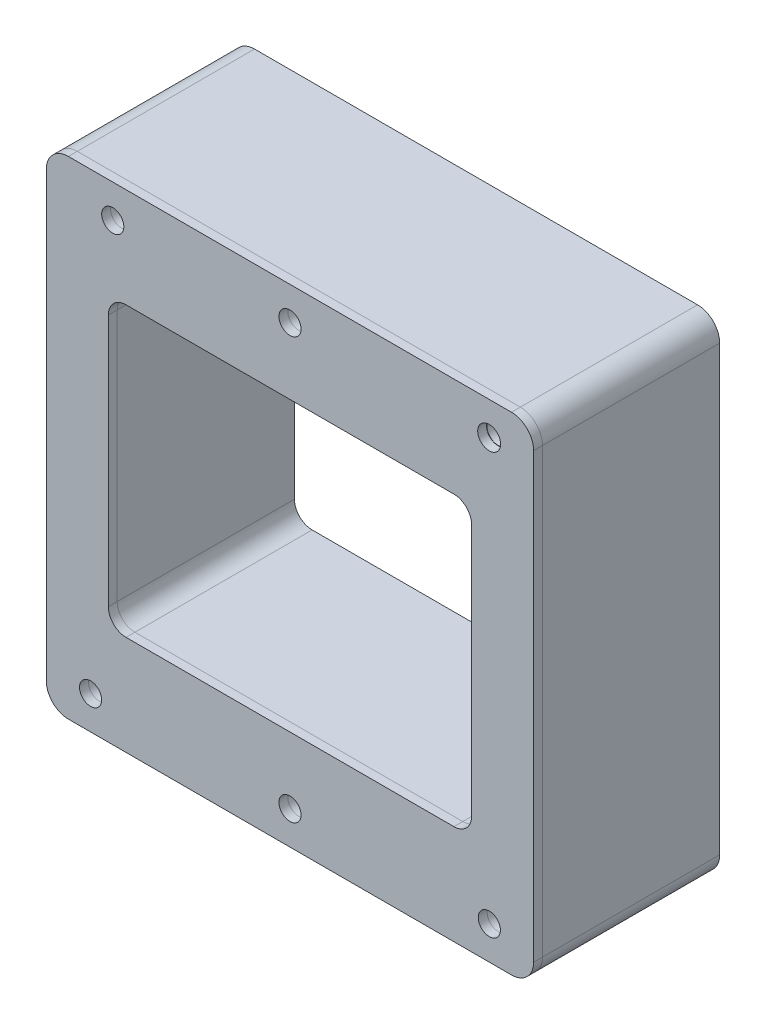
SolidWorks part; units mm, degrees
ref_plane "Front Plane" through (0, 0, 0) normal (0, 0, 1) x (1, 0, 0)
ref_plane "Top Plane" through (0, 0, 0) normal (0, 1, 0) x (1, 0, 0)
ref_plane "Right Plane" through (0, 0, 0) normal (1, 0, 0) x (0, 0, -1)
sketch "Croquis2" plane through (0, 0, 0) normal (0, 0, 1) x (1, 0, 0)
  line L16 (734.8657, 868.0574) -> (734.8657, 925.0574)
  line L17 (656.8657, 864.0574) -> (730.8657, 864.0574)
  line L18 (652.8657, 925.0574) -> (652.8657, 868.0574)
  line L19 (730.8657, 929.0574) -> (656.8657, 929.0574)
  line L24 (643.8623, 841.5574) -> (743.8623, 841.5574)
  line L25 (748.8623, 846.5574) -> (748.8623, 946.5574)
  line L26 (743.8623, 951.5574) -> (643.8623, 951.5574)
  line L27 (638.8623, 946.5574) -> (638.8623, 846.5574)
  circle A1 centre (693.8623, 944.0574) radius 2.5
  circle A2 centre (653.8623, 944.0574) radius 2.5
  circle A3 centre (738.8214, 944.0807) radius 2.5
  circle A4 centre (738.8623, 849.0574) radius 2.5
  circle A5 centre (693.8623, 849.0574) radius 2.5
  circle A6 centre (648.8623, 849.0574) radius 2.5
  arc A16 (730.8657, 864.0574) -> (734.8657, 868.0574) centre (730.8657, 868.0574) ccw
  arc A17 (652.8657, 868.0574) -> (656.8657, 864.0574) centre (656.8657, 868.0574) ccw
  arc A18 (656.8657, 929.0574) -> (652.8657, 925.0574) centre (656.8657, 925.0574) ccw
  arc A19 (734.8657, 925.0574) -> (730.8657, 929.0574) centre (730.8657, 925.0574) ccw
  arc A36 (743.8623, 841.5574) -> (748.8623, 846.5574) centre (743.8623, 846.5574) ccw
  arc A37 (748.8623, 946.5574) -> (743.8623, 951.5574) centre (743.8623, 946.5574) ccw
  arc A38 (643.8623, 951.5574) -> (638.8623, 946.5574) centre (643.8623, 946.5574) ccw
  arc A39 (638.8623, 846.5574) -> (643.8623, 841.5574) centre (643.8623, 846.5574) ccw
extrude "Saliente-Extruir1" add sketch "Croquis2" along normal blind 40
sketch "Croquis3" plane through (0, 0, 40) normal (0, 0, 1) x (1, 0, 0)
  line L4 (730.8657, 929.0574) -> (656.8657, 929.0574)
  line L5 (734.8657, 868.0574) -> (734.8657, 925.0574)
  line L6 (656.8657, 864.0574) -> (730.8657, 864.0574)
  line L7 (652.8657, 925.0574) -> (652.8657, 868.0574)
  line L8 (730.8657, 929.0574) -> (656.8657, 929.0574)
  line L9 (734.8657, 868.0574) -> (734.8657, 925.0574)
  line L10 (656.8657, 864.0574) -> (730.8657, 864.0574)
  line L11 (652.8657, 925.0574) -> (652.8657, 868.0574)
  line L12 (643.8623, 841.5574) -> (743.8623, 841.5574)
  line L13 (748.8623, 846.5574) -> (748.8623, 946.5574)
  line L14 (743.8623, 951.5574) -> (643.8623, 951.5574)
  line L15 (638.8623, 946.5574) -> (638.8623, 846.5574)
  line L16 (643.8623, 841.5574) -> (743.8623, 841.5574)
  line L17 (748.8623, 846.5574) -> (748.8623, 946.5574)
  line L18 (743.8623, 951.5574) -> (643.8623, 951.5574)
  line L19 (638.8623, 946.5574) -> (638.8623, 846.5574)
  circle A0 centre (653.8623, 944.0574) radius 2.5
  circle A1 centre (693.8623, 944.0574) radius 2.5
  circle A3 centre (738.8214, 944.0807) radius 2.585
  arc A4 (734.8657, 925.0574) -> (730.8657, 929.0574) centre (730.8657, 925.0574) ccw
  arc A5 (730.8657, 864.0574) -> (734.8657, 868.0574) centre (730.8657, 868.0574) ccw
  arc A6 (652.8657, 868.0574) -> (656.8657, 864.0574) centre (656.8657, 868.0574) ccw
  arc A7 (656.8657, 929.0574) -> (652.8657, 925.0574) centre (656.8657, 925.0574) ccw
  arc A8 (734.8657, 925.0574) -> (730.8657, 929.0574) centre (730.8657, 925.0574) ccw
  arc A9 (730.8657, 864.0574) -> (734.8657, 868.0574) centre (730.8657, 868.0574) ccw
  arc A10 (652.8657, 868.0574) -> (656.8657, 864.0574) centre (656.8657, 868.0574) ccw
  arc A11 (656.8657, 929.0574) -> (652.8657, 925.0574) centre (656.8657, 925.0574) ccw
  circle A13 centre (738.8623, 849.0574) radius 2.5
  circle A15 centre (693.8623, 849.0574) radius 2.5
  circle A17 centre (648.8623, 849.0574) radius 2.5
  arc A24 (638.8623, 846.5574) -> (643.8623, 841.5574) centre (643.8623, 846.5574) ccw
  arc A25 (743.8623, 841.5574) -> (748.8623, 846.5574) centre (743.8623, 846.5574) ccw
  arc A26 (748.8623, 946.5574) -> (743.8623, 951.5574) centre (743.8623, 946.5574) ccw
  arc A27 (643.8623, 951.5574) -> (638.8623, 946.5574) centre (643.8623, 946.5574) ccw
  arc A28 (638.8623, 846.5574) -> (643.8623, 841.5574) centre (643.8623, 846.5574) ccw
  arc A29 (743.8623, 841.5574) -> (748.8623, 846.5574) centre (743.8623, 846.5574) ccw
  arc A30 (748.8623, 946.5574) -> (743.8623, 951.5574) centre (743.8623, 946.5574) ccw
  arc A31 (643.8623, 951.5574) -> (638.8623, 946.5574) centre (643.8623, 946.5574) ccw
  dimension "D1" = 0
  dimension "D8" = 0
extrude "Saliente-Extruir2" add sketch "Croquis3" along normal blind 2 separate body
ref_plane "Plano1" through (0, 896.5574, 0) normal (0, 1, 0) x (1, 0, 0)
ref_plane "Plano2" through (693.8623, 0, 0) normal (1, 0, 0) x (0, 0, -1)
